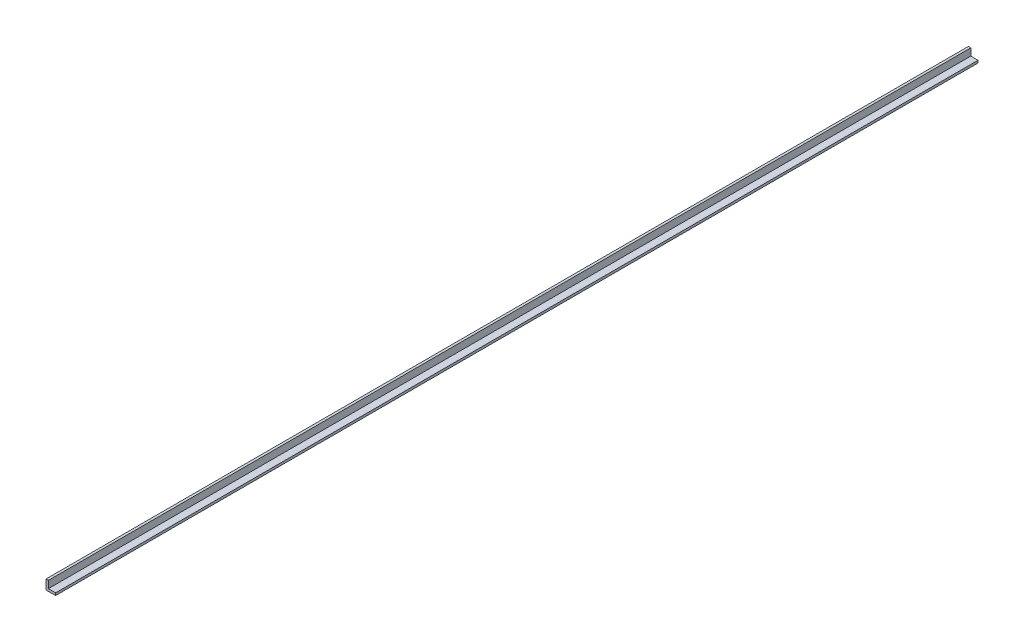
SolidWorks part; units mm, degrees
material "1060 Alloy"
ref_plane "Front Plane" through (0, 0, 0) normal (0, 0, 1) x (1, 0, 0)
ref_plane "Top Plane" through (0, 0, 0) normal (0, 1, 0) x (1, 0, 0)
ref_plane "Right Plane" through (0, 0, 0) normal (1, 0, 0) x (0, 0, -1)
sketch "Sketch1" plane through (0, 0, 0) normal (0, 0, 1) x (1, 0, 0)
  line L0 (0, 0) -> (0, 12.7)
  line L1 (0, 12.7) -> (3.175, 12.7)
  line L2 (3.175, 12.7) -> (3.175, 3.175)
  line L3 (3.175, 3.175) -> (12.7, 3.175)
  line L4 (12.7, 3.175) -> (12.7, 0)
  line L5 (12.7, 0) -> (0, 0)
  dimension "D1" = 12.7
  dimension "D2" = 3.175
extrude "Boss-Extrude1" add sketch "Sketch1" along normal mid plane 1219.2
